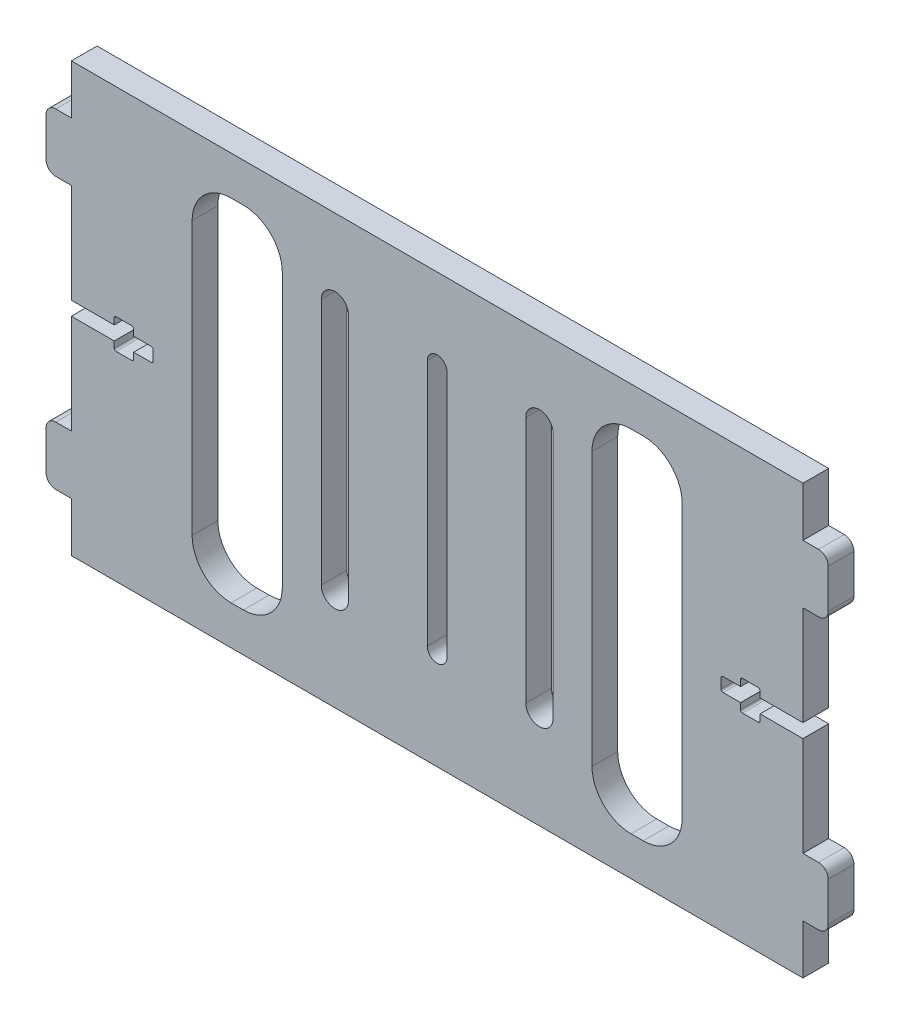
SolidWorks part; units mm, degrees
ref_plane "Front Plane" through (0, 0, 0) normal (0, 0, 1) x (1, 0, 0)
ref_plane "Top Plane" through (0, 0, 0) normal (0, 1, 0) x (1, 0, 0)
ref_plane "Right Plane" through (0, 0, 0) normal (1, 0, 0) x (0, 0, -1)
sketch "Model" plane through (0, 0, 0) normal (0, 0, 1) x (1, 0, 0)
  line L0 (29.75, 34.05) -> (29.75, -29.45)
  line L1 (22.75, -29.45) -> (22.75, 34.05)
  line L2 (-29.75, 34.05) -> (-29.75, -29.45)
  line L3 (-22.75, -29.45) -> (-22.75, 34.05)
  line L4 (72.9, 1.275) -> (72.9, -1.275)
  line L5 (73.4, -1.775) -> (77.9, -1.775)
  line L6 (77.9, -1.775) -> (77.9, -3.36)
  line L7 (78.4, -3.86) -> (82.4, -3.86)
  line L8 (82.9, -3.36) -> (82.9, -1.775)
  line L9 (82.9, -1.775) -> (93.9, -1.775)
  line L10 (93.9, -27.3) -> (93.9, -1.775)
  line L11 (93.9, -27.3) -> (97.9, -27.3)
  line L12 (100.4, -29.8) -> (100.4, -39.8)
  line L13 (97.9, -42.3) -> (93.9, -42.3)
  line L14 (93.9, -55) -> (93.9, -42.3)
  line L15 (-93.9, -55) -> (93.9, -55)
  line L16 (-93.9, -42.3) -> (-93.9, -55)
  line L17 (-97.9, -42.3) -> (-93.9, -42.3)
  line L18 (-100.4, -29.8) -> (-100.4, -39.8)
  line L19 (-93.9, -27.3) -> (-97.9, -27.3)
  line L20 (-93.9, -1.775) -> (-93.9, -27.3)
  line L21 (-93.9, -1.775) -> (-82.9, -1.775)
  line L22 (-82.9, -1.775) -> (-82.9, -3.36)
  line L23 (-82.4, -3.86) -> (-78.4, -3.86)
  line L24 (-77.9, -3.36) -> (-77.9, -1.775)
  line L25 (-77.9, -1.775) -> (-73.4, -1.775)
  line L26 (-72.9, -1.275) -> (-72.9, 1.275)
  line L27 (-73.4, 1.775) -> (-77.9, 1.775)
  line L28 (-77.9, 1.775) -> (-77.9, 3.36)
  line L29 (-78.4, 3.86) -> (-82.4, 3.86)
  line L30 (-82.9, 3.36) -> (-82.9, 1.775)
  line L31 (-82.9, 1.775) -> (-93.9, 1.775)
  line L32 (-93.9, 27.3) -> (-93.9, 1.775)
  line L33 (-97.9, 27.3) -> (-93.9, 27.3)
  line L34 (-100.4, 39.8) -> (-100.4, 29.8)
  line L35 (-93.9, 42.3) -> (-97.9, 42.3)
  line L36 (93.9, 55) -> (-93.9, 55)
  line L37 (93.9, 42.3) -> (93.9, 55)
  line L38 (100.4, 39.8) -> (100.4, 29.8)
  line L39 (93.9, 1.775) -> (82.9, 1.775)
  line L40 (82.9, 1.775) -> (82.9, 3.36)
  line L41 (82.4, 3.86) -> (78.4, 3.86)
  line L42 (77.9, 3.36) -> (77.9, 1.775)
  line L43 (77.9, 1.775) -> (73.4, 1.775)
  line L44 (2.54, -29.45) -> (2.54, 34.05)
  line L45 (-2.54, 34.05) -> (-2.54, -29.45)
  line L46 (-39.75, -35) -> (-39.75, 35)
  line L47 (-49.75, 45) -> (-52.9, 45)
  line L48 (-62.9, 35) -> (-62.9, -35)
  line L49 (-52.9, -45) -> (-49.75, -45)
  line L50 (62.9, -35) -> (62.9, 35)
  line L51 (52.9, 45) -> (49.75, 45)
  line L52 (39.75, 35) -> (39.75, -35)
  line L53 (49.75, -45) -> (52.9, -45)
  line L54 (-93.9, 55) -> (-93.9, 42.3)
  line L55 (97.9, 27.3) -> (93.9, 27.3)
  line L56 (93.9, 1.775) -> (93.9, 27.3)
  line L57 (93.9, 42.3) -> (97.9, 42.3)
  arc A0 (29.75, 34.05) -> (22.75, 34.05) centre (26.25, 34.05) ccw
  arc A1 (22.75, -29.45) -> (29.75, -29.45) centre (26.25, -29.45) ccw
  arc A2 (-22.75, 34.05) -> (-29.75, 34.05) centre (-26.25, 34.05) ccw
  arc A3 (-29.75, -29.45) -> (-22.75, -29.45) centre (-26.25, -29.45) ccw
  arc A4 (73.4, 1.775) -> (72.9, 1.275) centre (73.4, 1.275) ccw
  arc A5 (72.9, -1.275) -> (73.4, -1.775) centre (73.4, -1.275) ccw
  arc A6 (77.9, -3.36) -> (78.4, -3.86) centre (78.4, -3.36) ccw
  arc A7 (82.4, -3.86) -> (82.9, -3.36) centre (82.4, -3.36) ccw
  arc A8 (100.4, -29.8) -> (97.9, -27.3) centre (97.9, -29.8) ccw
  arc A9 (97.9, -42.3) -> (100.4, -39.8) centre (97.9, -39.8) ccw
  arc A10 (-100.4, -39.8) -> (-97.9, -42.3) centre (-97.9, -39.8) ccw
  arc A11 (-97.9, -27.3) -> (-100.4, -29.8) centre (-97.9, -29.8) ccw
  arc A12 (-82.9, -3.36) -> (-82.4, -3.86) centre (-82.4, -3.36) ccw
  arc A13 (-78.4, -3.86) -> (-77.9, -3.36) centre (-78.4, -3.36) ccw
  arc A14 (-73.4, -1.775) -> (-72.9, -1.275) centre (-73.4, -1.275) ccw
  arc A15 (-72.9, 1.275) -> (-73.4, 1.775) centre (-73.4, 1.275) ccw
  arc A16 (-77.9, 3.36) -> (-78.4, 3.86) centre (-78.4, 3.36) ccw
  arc A17 (-82.4, 3.86) -> (-82.9, 3.36) centre (-82.4, 3.36) ccw
  arc A18 (-100.4, 29.8) -> (-97.9, 27.3) centre (-97.9, 29.8) ccw
  arc A19 (-97.9, 42.3) -> (-100.4, 39.8) centre (-97.9, 39.8) ccw
  arc A20 (100.4, 39.8) -> (97.9, 42.3) centre (97.9, 39.8) ccw
  arc A21 (97.9, 27.3) -> (100.4, 29.8) centre (97.9, 29.8) ccw
  arc A22 (82.9, 3.36) -> (82.4, 3.86) centre (82.4, 3.36) ccw
  arc A23 (78.4, 3.86) -> (77.9, 3.36) centre (78.4, 3.36) ccw
  arc A24 (-2.54, -29.45) -> (2.54, -29.45) centre (0, -29.45) ccw
  arc A25 (2.54, 34.05) -> (-2.54, 34.05) centre (0, 34.05) ccw
  arc A26 (-49.75, -45) -> (-39.75, -35) centre (-49.75, -35) ccw
  arc A27 (-39.75, 35) -> (-49.75, 45) centre (-49.75, 35) ccw
  arc A28 (-52.9, 45) -> (-62.9, 35) centre (-52.9, 35) ccw
  arc A29 (-62.9, -35) -> (-52.9, -45) centre (-52.9, -35) ccw
  arc A30 (52.9, -45) -> (62.9, -35) centre (52.9, -35) ccw
  arc A31 (62.9, 35) -> (52.9, 45) centre (52.9, 35) ccw
  arc A32 (49.75, 45) -> (39.75, 35) centre (49.75, 35) ccw
  arc A33 (39.75, -35) -> (49.75, -45) centre (49.75, -35) ccw
extrude "Boss-Extrude1" add sketch "Model" along normal blind 6.6
